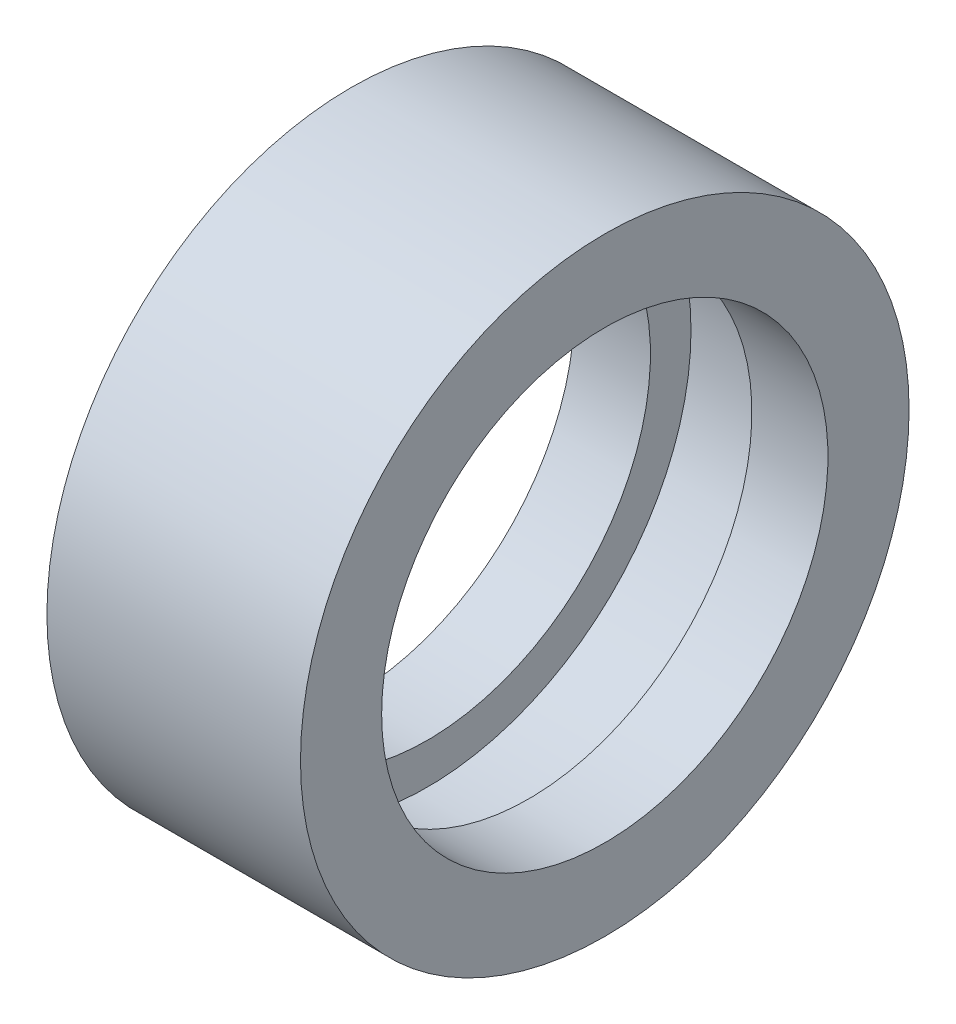
SolidWorks part; units mm, degrees
ref_plane "Plan de face" through (0, 0, 0) normal (0, 0, 1) x (1, 0, 0)
ref_plane "Plan de dessus" through (0, 0, 0) normal (0, 1, 0) x (1, 0, 0)
ref_plane "Plan de droite" through (0, 0, 0) normal (1, 0, 0) x (0, 0, -1)
sketch "Esquisse1" plane through (0, 0, 0) normal (0, 0, 1) x (1, 0, 0)
  line L0 (-51, 0) -> (52.1667, 0) construction
  line L1 (0, 37.6667) -> (0, -37.6667) construction
  line L2 (5, 22) -> (12.5, 22)
  line L3 (-12.5, 30) -> (12.5, 30)
  line L4 (-12.5, 30) -> (-12.5, 22)
  line L5 (-12.5, 22) -> (-5, 22)
  line L6 (12.5, 30) -> (12.5, 22)
  line L8 (5, 22) -> (5, 26)
  line L9 (5, 26) -> (-5, 26)
  line L10 (-5, 22) -> (-5, 26)
  dimension "D1" = 8
  dimension "D2" = 25
  dimension "D3" = 12.5
  dimension "D4" = 7.5
  dimension "D5" = 10
  dimension "D6" = 22
  dimension "D7" = 4
revolve "Révolution1" add sketch "Esquisse1" angle 360 about L0
